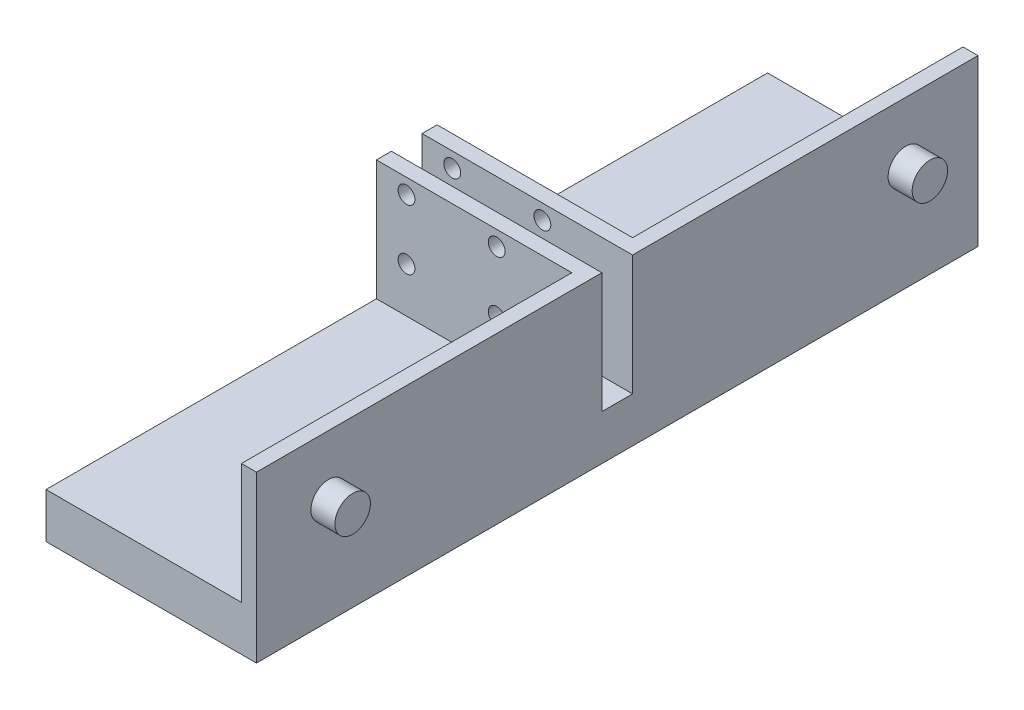
SolidWorks part; units mm, degrees
ref_plane "Front Plane" through (0, 0, 0) normal (0, 0, 1) x (1, 0, 0)
ref_plane "Top Plane" through (0, 0, 0) normal (0, 1, 0) x (1, 0, 0)
ref_plane "Right Plane" through (0, 0, 0) normal (1, 0, 0) x (0, 0, -1)
sketch "Sketch1" plane through (0, 0, 0) normal (0, 1, 0) x (1, 0, 0)
  line L1 (0, 60) -> (35, 60)
  line L2 (0, 60) -> (0, -60)
  line L3 (0, -60) -> (35, -60)
  line L4 (35, 60) -> (35, -60)
  point P4 (0, 0)
  dimension "D1" = 120
  dimension "D2" = 35
extrude "Boss-Extrude1" add sketch "Sketch1" along normal blind 7.5
sketch "Sketch2" plane through (0, 7.5, 0) normal (0, 1, 0) x (1, 0, 0)
  line L0 (35, -60) -> (35, 60) construction
  line L1 (35, 60) -> (32.5, 60)
  line L2 (35, 60) -> (35, 2.55)
  line L3 (35, 2.55) -> (32.5, 2.55)
  line L4 (32.5, 60) -> (32.5, 2.55)
  line L5 (35, -2.55) -> (32.5, -2.55)
  line L6 (35, -2.55) -> (35, -60)
  line L7 (35, -60) -> (32.5, -60)
  line L8 (32.5, -2.55) -> (32.5, -60)
  line L9 (0, -60) -> (35, -60) construction
  line L10 (0, 60) -> (0, -60) construction
  line L11 (32.5, -2.55) -> (0, -2.55)
  line L12 (32.5, -2.55) -> (32.5, -5.05)
  line L13 (32.5, -5.05) -> (0, -5.05)
  line L14 (0, -2.55) -> (0, -5.05)
  line L15 (16.25, 2.55) -> (16.25, -2.55) construction
  line L16 (32.5, 2.55) -> (0, 2.55)
  line L17 (32.5, 2.55) -> (32.5, 5.05)
  line L18 (32.5, 5.05) -> (0, 5.05)
  line L19 (0, 2.55) -> (0, 5.05)
  point P23 (16.25, 0)
  line M12 (0, 60) -> (0, -60)
  line M13 (0, -60) -> (35, -60)
  line M14 (35, -60) -> (35, 60)
  line M15 (35, 60) -> (0, 60)
  dimension "D1" = 2.5
  dimension "D2" = 2.5
  dimension "D3" = 5.1
extrude "Boss-Extrude2" add sketch "Sketch2" along normal blind 20 contours L4 L3 M15 M14 | L4 L18 L16 M12 | L13 L8 L11 M12 | L5 L8 M13 M14
sketch "Sketch3" plane through (0, 0, 5.05) normal (0, 0, 1) x (1, 0, 0)
  line L0 (5, 25) -> (20, 25) construction
  line L1 (20, 25) -> (20, 15) construction
  line L2 (20, 15) -> (5, 15) construction
  line L3 (5, 15) -> (5, 25) construction
  line L4 (0, 27.5) -> (0, 7.5) construction
  line L5 (32.5, 27.5) -> (0, 27.5) construction
  circle A0 centre (5, 25) radius 1.4
  circle A1 centre (5, 15) radius 1.4
  circle A2 centre (20, 25) radius 1.4
  circle A3 centre (20, 15) radius 1.4
  dimension "D1" = 2.8
  dimension "D2" = 15
  dimension "D3" = 10
  dimension "D4" = 5
  dimension "D5" = 2.5
extrude "Cut-Extrude1" cut sketch "Sketch3" against normal blind 12
sketch "Sketch4" plane through (35, 0, 0) normal (1, 0, 0) x (0, 0, -1)
  line L0 (-60, 27.5) -> (-2.55, 27.5) construction
  line L1 (-60, 27.5) -> (-60, 0) construction
  line L2 (0, 49.8613) -> (0, -10.001) construction
  circle A0 centre (-48, 17.5) radius 2.95
  circle A1 centre (48, 17.5) radius 2.95
  dimension "D1" = 5.9
  dimension "D2" = 10
  dimension "D3" = 12
extrude "Boss-Extrude3" add sketch "Sketch4" along normal blind 4
